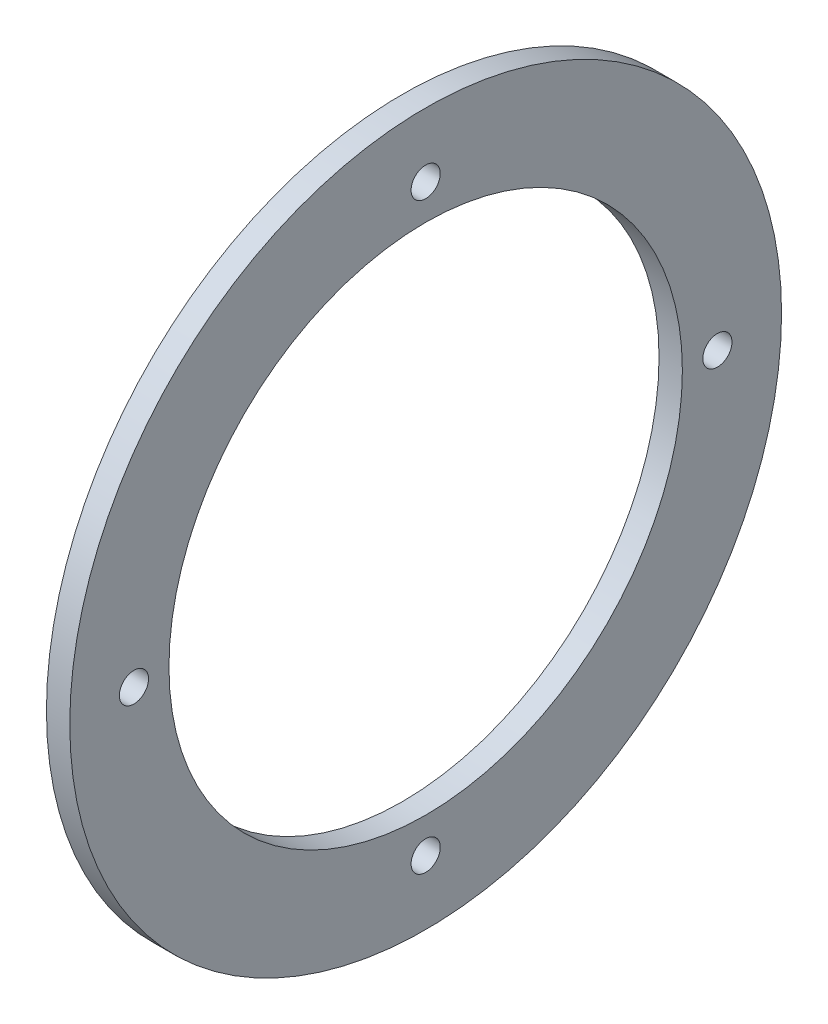
SolidWorks part; units mm, degrees
ref_plane "Front Plane" through (0, 0, 0) normal (0, 0, 1) x (1, 0, 0)
ref_plane "Top Plane" through (0, 0, 0) normal (0, 1, 0) x (1, 0, 0)
ref_plane "Right Plane" through (0, 0, 0) normal (1, 0, 0) x (0, 0, -1)
sketch "Sketch1" plane through (0, 0, 0) normal (1, 0, 0) x (0, 0, -1)
  line L2 (0, -46) -> (0, -50)
  circle A0 centre (0, 0) radius 44
  circle A1 centre (0, 0) radius 61
  circle A2 centre (0, -50) radius 2.5
  circle A3 centre (0, 50) radius 2.5
  circle A4 centre (-50, 0) radius 2.5
  circle A5 centre (50, 0) radius 2.5
  point P4 (0, 0)
  point P6 (0, 0)
  point P8 (0, 0)
  point P9 (0, 0)
  point P10 (0, -46)
  point P11 (0, 46)
  point P19 (0, 0)
  point P24 (0, 0)
  dimension "D2" = 122
  dimension "D4" = 5
  dimension "D3" = 4
extrude "Boss-Extrude1" add sketch "Sketch1" along normal blind 4
